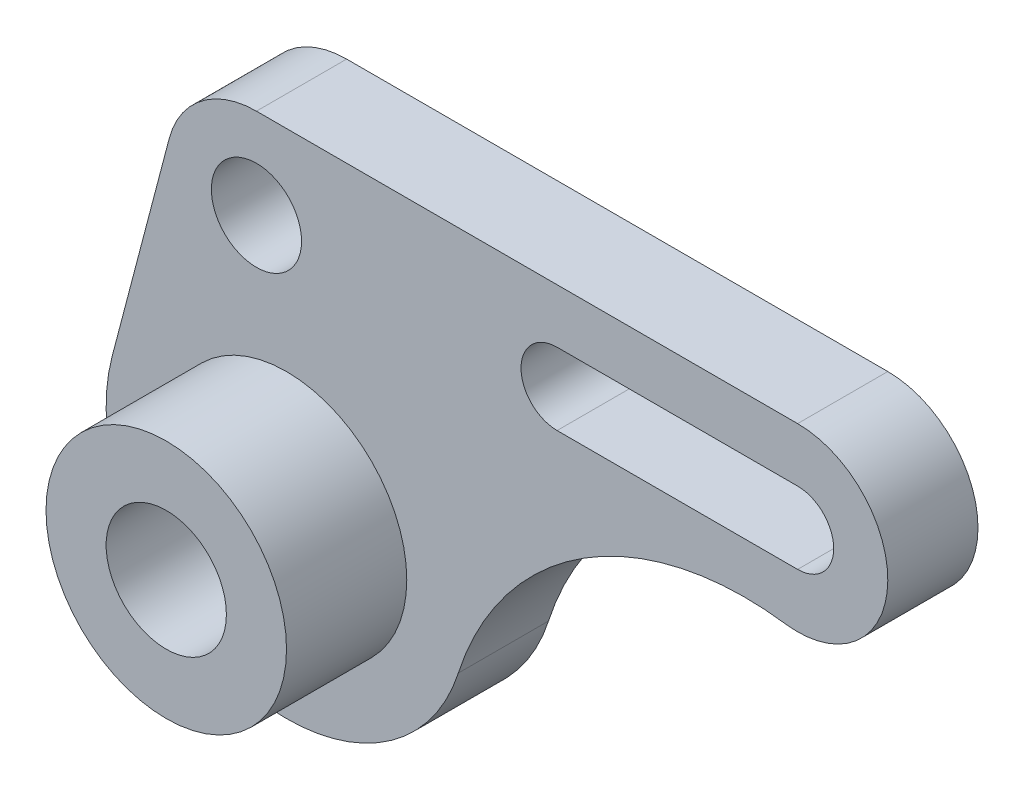
SolidWorks part; units mm, degrees
ref_plane "Front Plane" through (0, 0, 0) normal (0, 0, 1) x (1, 0, 0)
ref_plane "Top Plane" through (0, 0, 0) normal (0, 1, 0) x (1, 0, 0)
ref_plane "Right Plane" through (0, 0, 0) normal (1, 0, 0) x (0, 0, -1)
sketch "Sketch1" plane through (0, 0, 0) normal (0, 0, 1) x (1, 0, 0)
  line L0 (85, 40) -> (45, 40) construction
  line L1 (85, 34) -> (45, 34)
  line L2 (85, 46) -> (45, 46)
  line L3 (-29.0153, 7.6231) -> (-19.5077, 43.8115)
  line L4 (-5, 55) -> (85, 55)
  line L5 (85, 55) -> (-5, 55)
  circle A0 centre (0, 0) radius 10
  arc A1 (-29.0153, 7.6231) -> (28.5706, -9.15) centre (0, 0) ccw
  circle A2 centre (-5, 40) radius 7.5
  arc A3 (82.9665, 25.1385) -> (28.5706, -9.15) centre (76.1882, -24.3999) ccw
  arc A4 (82.9665, 25.1385) -> (85, 55) centre (85, 40) ccw
  arc A5 (85, 34) -> (85, 46) centre (85, 40) ccw
  arc A6 (45, 46) -> (45, 34) centre (45, 40) ccw
  arc A7 (-5, 55) -> (-19.5077, 43.8115) centre (-5, 40) ccw
  point P3 (0, 0)
  point P7 (0, 0)
  point P9 (0, 0)
  point P10 (65, 40)
  point P16 (0, 0)
  point P23 (0, 0)
  point P24 (0, 0)
  dimension "D1" = 60
  dimension "D2" = 20
  dimension "D3" = 15
  dimension "D4" = 50
  dimension "D5" = 30
  dimension "D7" = 6
  dimension "D11" = 30
  dimension "D12" = 85
  dimension "D6" = 40
  dimension "D8" = 40
  dimension "D9" = 50
  dimension "D10" = 0
  dimension "D13" = 90
extrude "Boss-Extrude1" add sketch "Sketch1" along normal mid plane 15 contours L4 A7 L3 A1 A3 A4 A0 A2 A6 L2 A5 L1
sketch "Sketch2" plane through (0, 0, 0) normal (0, 0, 1) x (1, 0, 0)
  circle A0 centre (0, 0) radius 20
  circle A1 centre (0, 0) radius 10
  dimension "D1" = 40
  dimension "D2" = 20
extrude "Boss-Extrude2" add sketch "Sketch2" along normal blind 20 from offset 7.5
